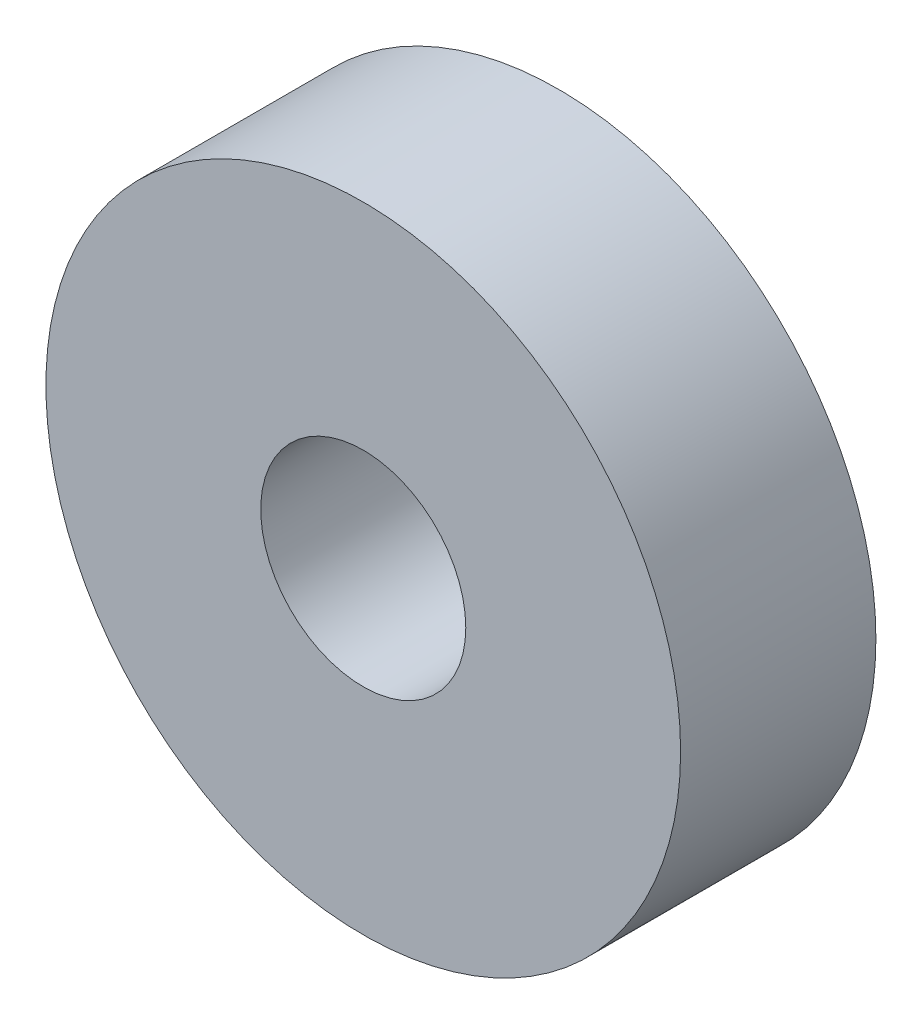
SolidWorks part; units mm, degrees
ref_plane "Front Plane" through (0, 0, 0) normal (0, 0, 1) x (1, 0, 0)
ref_plane "Top Plane" through (0, 0, 0) normal (0, 1, 0) x (1, 0, 0)
ref_plane "Right Plane" through (0, 0, 0) normal (1, 0, 0) x (0, 0, -1)
sketch "Sketch1" plane through (0, 0, 0) normal (0, 0, 1) x (1, 0, 0)
  circle A0 centre (0, 0) radius 6.5
  circle A1 centre (0, 0) radius 2.1
  dimension "D1" = 13
  dimension "D2" = 4.2
extrude "Boss-Extrude1" add sketch "Sketch1" along normal blind 4
